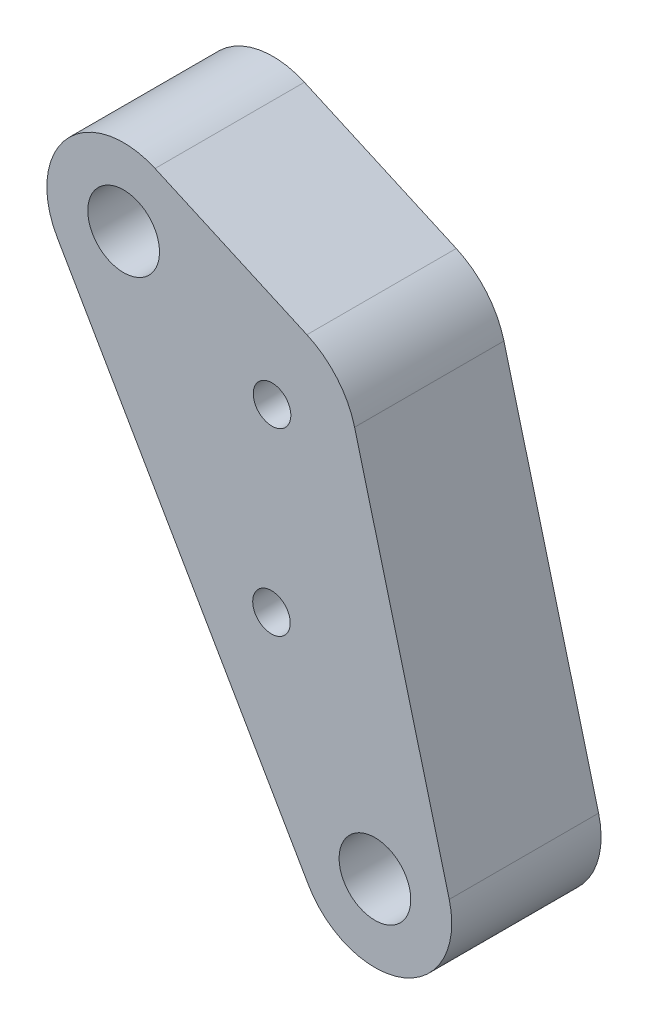
SolidWorks part; units mm, degrees
ref_plane "Front Plane" through (0, 0, 0) normal (0, 0, 1) x (1, 0, 0)
ref_plane "Top Plane" through (0, 0, 0) normal (0, 1, 0) x (1, 0, 0)
ref_plane "Right Plane" through (0, 0, 0) normal (1, 0, 0) x (0, 0, -1)
ref_plane "Plane1" through (0, 0, 17.5) normal (0, 0, 1) x (1, 0, 0)
sketch "Sketch1" plane through (0, 0, 17.5) normal (0, 0, 1) x (1, 0, 0)
  line L0 (8.7067, -31.7211) -> (-3.5966, 15.2836)
  line L1 (-3.5966, 15.2836) -> (-25.7658, 25.2137)
  line L2 (-37.2391, 12.5) -> (-7.7942, -38.5)
  arc A0 (-25.7658, 25.2137) -> (-37.2391, 12.5) centre (-29.4449, 17) ccw
  arc A1 (-7.7942, -38.5) -> (8.7067, -31.7211) centre (0, -34) ccw
extrude "Boss-Extrude1" add sketch "Sketch1" against normal blind 17.5
sketch "Sketch2" plane through (-22.5167, -13, 0) normal (-0.866, -0.5, 0) x (0, 0, 1)
  line L0 (9.792, 18.3659) -> (10.9093, 19.4449)
  line L1 (10.9093, 19.4449) -> (9.792, 20.5239)
  arc A0 (9.792, 20.5239) -> (9.792, 18.3659) centre (8.75, 19.4449) ccw
extrude "Cut-Extrude1" cut sketch "Sketch2" against normal blind 1
hole_wizard "Hole1" positions "Sketch4" profile "Sketch3" legacy
sketch "Sketch4" plane through (0, 0, 0) normal (0, 0, -1) x (-1, 0, 0)
  point P0 (12.0574, 8.116)
sketch "Sketch3" plane through (-12.0574, 8.116, 0) normal (1, 0, 0) x (0, 1, 0)
  line L0 (0, 0) -> (0, 17.5)
  line L1 (0, 17.5) -> (2.2, 17.5)
  line L2 (2.2, 17.5) -> (2.2, 0)
  line L3 (2.2, 0) -> (0, 0)
  line L4 (0, 110) -> (0, -10) construction
  dimension "Diameter" = 4.4
  dimension "Depth" = 17.5
hole_wizard "Hole2" positions "Sketch6" profile "Sketch5" legacy
sketch "Sketch6" plane through (0, 0, 0) normal (0, 0, -1) x (-1, 0, 0)
  point P0 (12.1244, -13)
sketch "Sketch5" plane through (-12.1244, -13, 0) normal (1, 0, 0) x (0, 1, 0)
  line L0 (0, 0) -> (0, 17.5)
  line L1 (0, 17.5) -> (2.2, 17.5)
  line L2 (2.2, 17.5) -> (2.2, 0)
  line L3 (2.2, 0) -> (0, 0)
  line L4 (0, 110) -> (0, -10) construction
  dimension "Diameter" = 4.4
  dimension "Depth" = 17.5
hole_wizard "Hole3" positions "Sketch8" profile "Sketch7" legacy
sketch "Sketch8" plane through (0, 0, 0) normal (0, 0, -1) x (-1, 0, 0)
  point P0 (0, -34)
sketch "Sketch7" plane through (0, -34, 0) normal (1, 0, 0) x (0, 1, 0)
  line L0 (0, 0) -> (0, 17.5)
  line L1 (0, 17.5) -> (4.2, 17.5)
  line L2 (4.2, 17.5) -> (4.2, 0)
  line L3 (4.2, 0) -> (0, 0)
  line L4 (0, 110) -> (0, -10) construction
  dimension "Diameter" = 8.4
  dimension "Depth" = 17.5
hole_wizard "Hole4" positions "Sketch10" profile "Sketch9" legacy
sketch "Sketch10" plane through (0, 0, 0) normal (0, 0, -1) x (-1, 0, 0)
  point P0 (29.4449, 17)
sketch "Sketch9" plane through (-29.4449, 17, 0) normal (1, 0, 0) x (0, 1, 0)
  line L0 (0, 0) -> (0, 17.5)
  line L1 (0, 17.5) -> (4.2, 17.5)
  line L2 (4.2, 17.5) -> (4.2, 0)
  line L3 (4.2, 0) -> (0, 0)
  line L4 (0, 110) -> (0, -10) construction
  dimension "Diameter" = 8.4
  dimension "Depth" = 17.5
fillet "Fillet1" radius 10 1 edges at (-3.5966, 15.2836, 8.75)
